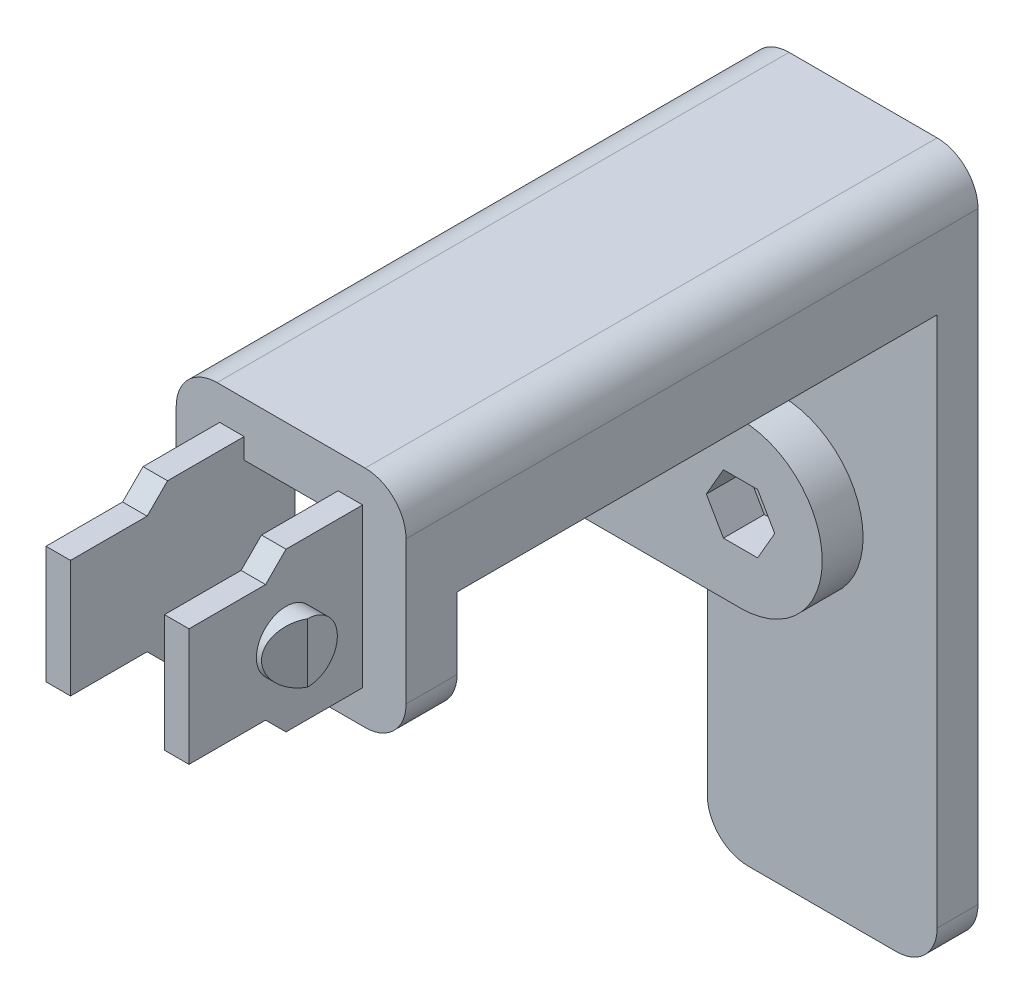
SolidWorks part; units mm, degrees
material "PET"
ref_plane "Front Plane" through (0, 0, 0) normal (0, 0, 1) x (1, 0, 0)
ref_plane "Top Plane" through (0, 0, 0) normal (0, 1, 0) x (1, 0, 0)
ref_plane "Right Plane" through (0, 0, 0) normal (1, 0, 0) x (0, 0, -1)
sketch "Sketch1" plane through (0, 0, 0) normal (0, 0, 1) x (1, 0, 0)
  line L2 (-17, -8) -> (-17, 8)
  line L4 (-17, 8) -> (-11.25, 8)
  line L17 (-3.25, 33.5) -> (11.25, 33.5)
  line L21 (-3.25, -33.5) -> (11.25, -33.5)
  line L23 (15.25, -29.5) -> (15.25, 29.5)
  line L24 (-7.25, 29.5) -> (-7.25, 12)
  line L25 (-17, -8) -> (-11.25, -8)
  line L26 (-7.25, -12) -> (-7.25, -29.5)
  circle A0 centre (0, 0) radius 1.65
  arc A2 (11.25, 33.5) -> (15.25, 29.5) centre (11.25, 29.5) cw
  arc A3 (-3.25, 33.5) -> (-7.25, 29.5) centre (-3.25, 29.5) ccw
  arc A4 (-11.25, -8) -> (-7.25, -12) centre (-11.25, -12) cw
  arc A5 (-11.25, 8) -> (-7.25, 12) centre (-11.25, 12) ccw
  arc A6 (-3.25, -33.5) -> (-7.25, -29.5) centre (-3.25, -29.5) cw
  arc A7 (11.25, -33.5) -> (15.25, -29.5) centre (11.25, -29.5) ccw
  dimension "D1" = 4
extrude "Boss-Extrude1" add sketch "Sketch1" along normal blind 75
sketch "Sketch4" plane through (15.25, 0, 0) normal (1, 0, 0) x (0, 0, -1)
  line L4 (-75, 11.5) -> (-75, -33.5)
  line L5 (-75, 11.5) -> (-53, 11.5)
  line L6 (-53, 11.5) -> (-53, 22.5)
  line L14 (-10, 8) -> (-10, -8)
  line L25 (-75, -33.5) -> (-6, -33.5)
  line L31 (-53, 22.5) -> (-6, 22.5)
  line L42 (-10, 8) -> (-6, 8)
  line L43 (-6, 22.5) -> (-6, 8)
  line L44 (-10, -8) -> (-6, -8)
  line L47 (-6, -8) -> (-6, -33.5)
extrude "Cut-Extrude3" cut sketch "Sketch4" against normal up to surface (32.25 mm away) up to face at (-17, 0, 37.5)
sketch "Sketch5" plane through (0, 0, 75) normal (0, 0, 1) x (1, 0, 0)
  line L0 (-0.6, 28.25) -> (8.6, 28.25)
  line L1 (-0.6, 28.25) -> (-0.6, 16.75)
  line L2 (-0.6, 16.75) -> (8.6, 16.75)
  line L3 (8.6, 28.25) -> (8.6, 16.75)
  line L5 (11.25, 11.5) -> (15.25, 11.5)
  line L6 (-7.2814, 11.5) -> (-3.25, 11.5)
  line L8 (15.25, 15.5) -> (15.25, 11.5)
  line L9 (-7.25, 15.5) -> (-7.25, 12)
  line L11 (0, 8) -> (15.25, 8)
  line L12 (15.25, 8) -> (15.25, -8)
  line L13 (15.25, -8) -> (0, -8)
  arc A3 (11.25, 11.5) -> (15.25, 15.5) centre (11.25, 15.5) ccw
  arc A4 (-7.25, 15.5) -> (-3.25, 11.5) centre (-3.25, 15.5) ccw
  arc A5 (-7.2814, 11.5) -> (-7.25, 12) centre (-11.25, 12) ccw
  arc A6 (0, -8) -> (0, 8) centre (0, 0) ccw
extrude "Cut-Extrude4" cut sketch "Sketch5" against normal up to surface (69 mm away) up to face at (1.1157, 14.4343, 6)
sketch "Sketch6" plane through (0, 0, 6) normal (0, 0, 1) x (1, 0, 0)
  line L5 (-1.75, 28.25) -> (9.75, 28.25)
  line L6 (-1.75, 28.25) -> (-1.75, 16.75)
  line L7 (-1.75, 16.75) -> (9.75, 16.75)
  line L8 (9.75, 28.25) -> (9.75, 16.75)
extrude "Cut-Extrude5" cut sketch "Sketch6" along normal up to surface (47 mm away) up to face at (4, 17.5843, 53)
sketch "Sketch7" plane through (0, 0, 0) normal (0, 0, -1) x (-1, 0, 0)
  line L3 (-15.25, 33.5) -> (15, 33.5)
  line L4 (-15.25, 33.5) -> (-15.25, -33.5)
  line L5 (-15.25, -33.5) -> (15, -33.5)
  line L6 (15, 33.5) -> (15, -33.5)
extrude "Cut-Extrude6" cut sketch "Sketch7" against normal blind 2
sketch "Sketch8" plane through (0, 0, 10) normal (0, 0, 1) x (1, 0, 0)
  line L7 (3.3486, 0) -> (1.6743, 2.9)
  line L8 (1.6743, 2.9) -> (-1.6743, 2.9)
  line L9 (-1.6743, 2.9) -> (-3.3486, 0)
  line L10 (-3.3486, 0) -> (-1.6743, -2.9)
  line L11 (-1.6743, -2.9) -> (1.6743, -2.9)
  line L12 (1.6743, -2.9) -> (3.3486, 0)
  circle A0 centre (0, 0) radius 2.9 construction
extrude "Cut-Extrude7" cut sketch "Sketch8" against normal offset from surface (4 mm away) 4 up to face at (-1.65, 0, 2)
sketch "Sketch9" plane through (15.25, 0, 0) normal (1, 0, 0) x (0, 0, -1)
  line L8 (-75, 33.5) -> (-58, 33.5)
  line L9 (-75, 33.5) -> (-75, 11.5)
  line L10 (-75, 11.5) -> (-58, 11.5)
  line L11 (-58, 33.5) -> (-58, 11.5)
  circle A1 centre (-65.5, 22.5) radius 2.9
extrude "Cut-Extrude8" cut sketch "Sketch9" against normal offset from surface (4.25 mm away) 2.4 up to face at (8.6, 22.5, 64)
sketch "Sketch10" plane through (-7.25, 0, 0) normal (-1, 0, 0) x (0, 0, 1)
  line L1 (75, 33.5) -> (75, 11.5)
  line L4 (58, 33.5) -> (58, 11.5)
  line L5 (75, 11.5) -> (58, 11.5)
  line L6 (75, 33.5) -> (58, 33.5)
  circle A1 centre (65.5, 22.5) radius 2.9
extrude "Cut-Extrude9" cut sketch "Sketch10" against normal offset from surface (4.25 mm away) 2.4 up to face at (-0.6, 22.5, 64)
sketch "Sketch11" plane through (0, 0, 75) normal (0, 0, 1) x (1, 0, 0)
  line L0 (-7.25, 14.75) -> (-7.25, 11.5)
  line L1 (-7.25, 11.5) -> (15.25, 11.5)
  line L2 (-7.25, 33.5) -> (15.25, 33.5)
  line L3 (15.25, 11.5) -> (15.25, 14.75)
  line L4 (-7.25, 33.5) -> (-7.25, 30.25)
  line L5 (15.25, 33.5) -> (15.25, 30.25)
  line L6 (-0.6, 14.75) -> (-0.6, 30.25)
  line L7 (8.6, 14.75) -> (8.6, 30.25)
  line L8 (-7.25, 14.75) -> (-0.6, 14.75)
  line L9 (15.25, 14.75) -> (8.6, 14.75)
  line L10 (-7.25, 30.25) -> (-0.6, 30.25)
  line L11 (15.25, 30.25) -> (8.6, 30.25)
extrude "Cut-Extrude10" cut sketch "Sketch11" against normal up to surface (17 mm away) up to face at (-4.7761, 22.5, 58)
sketch "Sketch12" plane through (-7.25, 0, 0) normal (-1, 0, 0) x (0, 0, 1)
  line L0 (65.5, 30.25) -> (67.5, 28.25)
  line L1 (67.5, 28.25) -> (75, 28.25)
  line L2 (65.5, 14.75) -> (67.5, 16.75)
  line L3 (67.5, 16.75) -> (75, 16.75)
  line L4 (65.5, 30.25) -> (75, 30.25)
  line L5 (75, 30.25) -> (75, 28.25)
  line L6 (65.5, 14.75) -> (75, 14.75)
  line L7 (75, 14.75) -> (75, 16.75)
extrude "Cut-Extrude11" cut sketch "Sketch12" against normal up to surface (22.5 mm away)
sketch "Sketch13" plane through (0, 33.5, 0) normal (0, 1, 0) x (1, 0, 0)
  line L0 (-5.1, -65.5) -> (-3.5, -68.4)
  line L1 (-5.125, -62.6) -> (-5.1, -65.5)
  line L2 (13.1, -65.5) -> (11.5, -68.4)
  line L3 (-7.25, -62.6) -> (-5.125, -62.6)
  line L4 (-7.25, -62.6) -> (-7.25, -68.4)
  line L5 (-7.25, -68.4) -> (-3.5, -68.4)
  line L6 (13.125, -62.6) -> (13.1, -65.5)
  line L7 (15.25, -62.6) -> (13.125, -62.6)
  line L8 (11.5, -68.4) -> (15.25, -68.4)
  line L9 (15.25, -68.4) -> (15.25, -62.6)
extrude "Cut-Extrude12" cut sketch "Sketch13" against normal up to surface (22 mm away) up to face at (4, 11.5, 55.5)
